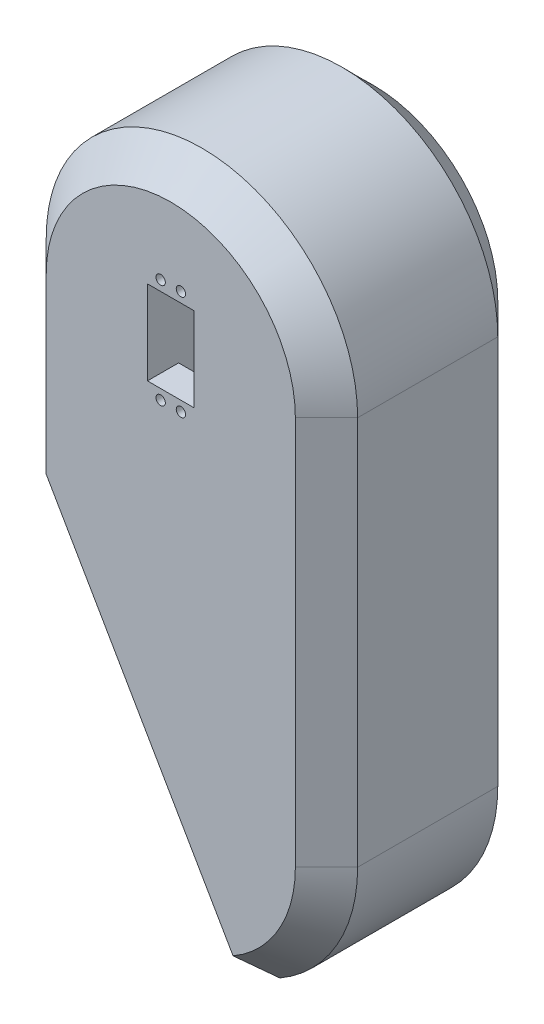
SolidWorks part; units mm, degrees
ref_plane "Front Plane" through (0, 0, 0) normal (0, 0, 1) x (1, 0, 0)
ref_plane "Top Plane" through (0, 0, 0) normal (0, 1, 0) x (1, 0, 0)
ref_plane "Right Plane" through (0, 0, 0) normal (1, 0, 0) x (0, 0, -1)
sketch "Sketch1" plane through (0, 0, 0) normal (0, 0, 1) x (1, 0, 0)
  line L0 (0, 0) -> (608.8114, 0) construction
  line L1 (0, 0) -> (0, 125) construction
  line L2 (-50, 125) -> (-50, 0)
  line L3 (50, 125) -> (50, 0)
  arc A1 (-50, 0) -> (50, 0) centre (0, 0) ccw
  arc A2 (50, 125) -> (-50, 125) centre (0, 125) ccw
  dimension "D1" = 100
  dimension "D2" = 100
  dimension "D3" = 125
extrude "Boss-Extrude1" add sketch "Sketch1" along normal blind 65
sketch "Sketch2" plane through (0, 0, 65) normal (0, 0, 1) x (1, 0, 0)
  line L0 (0, -50) -> (0, 330.4838) construction
  line L1 (25, -43.3013) -> (-173.3169, 300.1936) construction
  line L2 (25, -43.3013) -> (-50, 86.6025)
  line L4 (-50, 125) -> (-50, 0) construction
  line L6 (-50, 86.6025) -> (-50, 0)
  arc A2 (-50, 0) -> (50, 0) centre (0, 0) ccw construction
  dimension "D1" = 30
extrude "Cut-Extrude1" cut sketch "Sketch2" against normal through all
sketch "Sketch5" plane through (0, 0, 0) normal (-0.866, -0.5, 0) x (0, 0, 1)
  line L0 (32.5, -50) -> (32.5, 100) construction
  line L1 (0, -50) -> (65, -50) construction
  line L2 (0, 100) -> (65, 100) construction
  circle A0 centre (32.5, 25) radius 15
  dimension "D1" = 30
extrude "Cut-Extrude4" cut sketch "Sketch5" against normal blind 5
sketch "Sketch6" plane through (4.3301, 2.5, 0) normal (-0.866, -0.5, 0) x (0, 0, 1)
  line L0 (32.5, 10) -> (32.5, 40) construction
  line L1 (47.5, 25) -> (17.5, 25) construction
  circle A0 centre (40, 25) radius 1.5
  circle A2 centre (32.5, 25) radius 15 construction
  circle A3 centre (32.5, 32.5) radius 1.5
  circle A4 centre (32.5, 17.5) radius 1.5
  circle A5 centre (25, 25) radius 1.5
  point P11 (32.5, 25)
  point P19 (32.5, 25)
  dimension "D1" = 3
  dimension "D2" = 7.5
  dimension "D3" = 4
extrude "Cut-Extrude5" cut sketch "Sketch6" against normal blind 7.5
chamfer "Chamfer1" distance 10 angle 45 8 edges at (-50, 105.8013, 65) (0, 175, 65) (43.3013, -25, 65) (50, 62.5, 65) (-50, 105.8013, 0) (0, 175, 0) (43.3013, -25, 0) (50, 62.5, 0)
sketch "Sketch8" plane through (0, 0, 0) normal (0, 0, -1) x (-1, 0, 0)
  line L0 (0, 0) -> (0, 316.1606) construction
  line L2 (-7.5, 145) -> (7.5, 145)
  line L3 (-7.5, 145) -> (-7.5, 105)
  line L4 (-7.5, 105) -> (7.5, 105)
  line L5 (7.5, 145) -> (7.5, 105)
  line L6 (-7.5, 145) -> (7.5, 105) construction
  line L7 (-7.5, 105) -> (7.5, 145) construction
  point P3 (0, 125)
  dimension "D1" = 40
  dimension "D2" = 15
extrude "Cut-Extrude6" cut sketch "Sketch8" against normal offset from surface (55 mm away) 10 up to face at (4.9282, 64.3923, 65)
sketch "Sketch9" plane through (0, 0, 55) normal (0, 0, -1) x (-1, 0, 0)
  line L0 (7.5, 105) -> (7.5, 145) construction
  line L1 (-7.5, 145) -> (7.5, 145)
  line L2 (-7.5, 145) -> (-7.5, 138.5)
  line L3 (-7.5, 138.5) -> (7.5, 138.5)
  line L4 (7.5, 145) -> (7.5, 138.5)
  line L5 (0, 105) -> (0, 145) construction
  line L6 (-7.5, 105) -> (7.5, 105)
  line L7 (-7.5, 105) -> (-7.5, 111.5)
  line L8 (-7.5, 111.5) -> (7.5, 111.5)
  line L9 (7.5, 105) -> (7.5, 111.5)
  line L10 (7.5, 125) -> (-7.5, 125) construction
  line L11 (-7.5, 145) -> (-7.5, 105) construction
  line L12 (-7.5, 111.5) -> (-7.5, 138.5)
  line L13 (7.5, 111.5) -> (7.5, 138.5)
  circle A0 centre (-3.25, 141.75) radius 1.5
  circle A1 centre (3.25, 141.75) radius 1.5
  circle A2 centre (3.25, 108.25) radius 1.5
  circle A3 centre (-3.25, 108.25) radius 1.5
  line M12 (7.5, 105) -> (7.5, 145)
  line M14 (-7.5, 145) -> (-7.5, 105)
  dimension "D3" = 3
  dimension "D1" = 6.5
  dimension "D2" = 6.5
  dimension "D4" = 3.25
  dimension "D5" = 3.25
extrude "Cut-Extrude7" cut sketch "Sketch9" against normal through all contours L8 L3 M14 M12 | A3 | A2 | A0 | A1
sketch "Sketch10" plane through (0, 0, 65) normal (0, 0, 1) x (1, 0, 0)
  line L0 (0, 109.5) -> (0, 138.5) construction
  line L2 (7.5, 138.5) -> (-7.5, 138.5) construction
  circle A0 centre (0, 125) radius 3.75 construction
  point P3 (0, 124)
  dimension "D1" = 7.5
fillet "Fillet1" radius 1 2 edges at (-0.6699, 11.1603, 32.5) (-5, 8.6603, 32.5)
